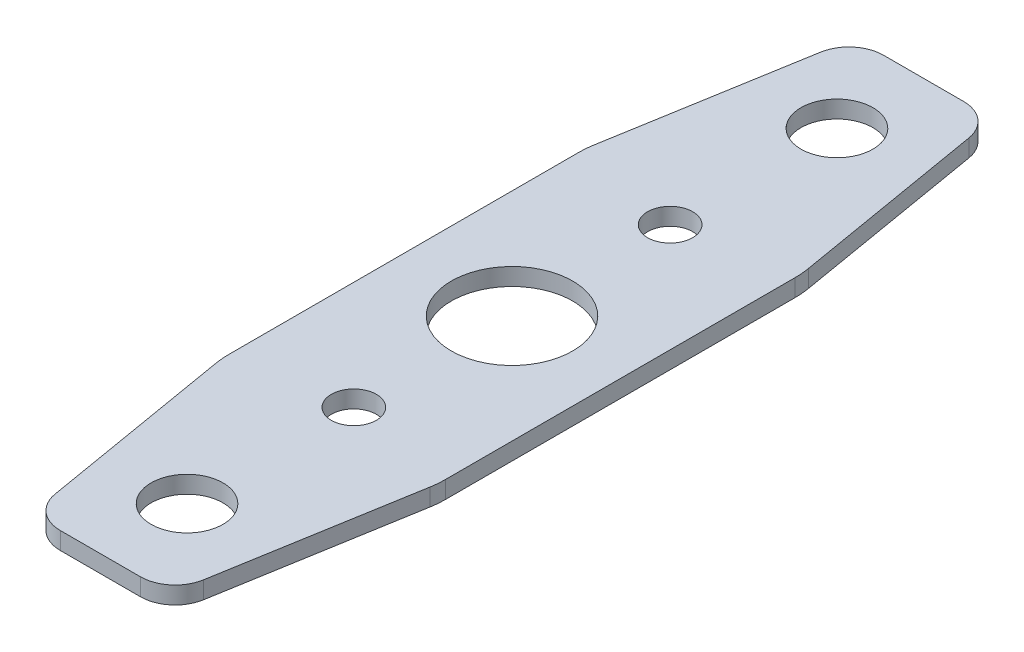
SolidWorks part; units mm, degrees
ref_plane "Front Plane" through (0, 0, 0) normal (0, 0, 1) x (1, 0, 0)
ref_plane "Top Plane" through (0, 0, 0) normal (0, 1, 0) x (1, 0, 0)
ref_plane "Right Plane" through (0, 0, 0) normal (1, 0, 0) x (0, 0, -1)
sketch "Sketch1" plane through (0, 0, 0) normal (0, 1, 0) x (1, 0, 0)
  line L0 (0, 54.328) -> (0, -44.5641) construction
  line L1 (-25.1307, 0) -> (26.2682, 0) construction
  line L2 (-4.622, 47.5) -> (4.622, 47.5)
  line L3 (-12.5, -21) -> (12.5, -21)
  line L4 (-12.5, -21) -> (-12.5, 21)
  line L5 (-12.5, 21) -> (12.5, 21)
  line L6 (12.5, -21) -> (12.5, 21)
  line L7 (-12.5, -21) -> (12.5, 21) construction
  line L8 (-12.5, 21) -> (12.5, -21) construction
  line L9 (8.5655, 44.1697) -> (12.5, 21)
  line L10 (-8.5655, 44.1697) -> (-12.5, 21)
  line L11 (-8.5655, -44.1697) -> (-12.5, -21)
  line L12 (8.5655, -44.1697) -> (12.5, -21)
  line L13 (-4.622, -47.5) -> (4.622, -47.5)
  circle A0 centre (0, 0) radius 7
  circle A5 centre (0, 37.5) radius 4.15
  arc A6 (8.5655, 44.1697) -> (4.622, 47.5) centre (4.622, 43.5) ccw
  arc A7 (-8.5655, -44.1697) -> (-4.622, -47.5) centre (-4.622, -43.5) ccw
  arc A8 (-8.5655, 44.1697) -> (-4.622, 47.5) centre (-4.622, 43.5) cw
  arc A9 (8.5655, -44.1697) -> (4.622, -47.5) centre (4.622, -43.5) cw
  circle A10 centre (0, -37.5) radius 4.15
  circle A11 centre (0, 18.25) radius 2.6
  circle A12 centre (0, -18.25) radius 2.6
  point P27 (8, 47.5)
  point P31 (0, 47.5)
  point P37 (0, -47.5)
  point P38 (8, -47.5)
  dimension "D1" = 14
  dimension "D3" = 8
  dimension "D7" = 8.3
  dimension "D8" = 16.5
  dimension "D9" = 10
  dimension "D10" = 4
  dimension "D11" = 5.2
  dimension "D12" = 36.5
  dimension "D5" = 42
  dimension "D6" = 25
extrude "Boss-Extrude1" add sketch "Sketch1" along normal blind 2
fillet "Fillet1" radius 10 4 edges at (-12.5, 1, -21) (-12.5, 1, 21) (12.5, 1, 21) (12.5, 1, -21)
